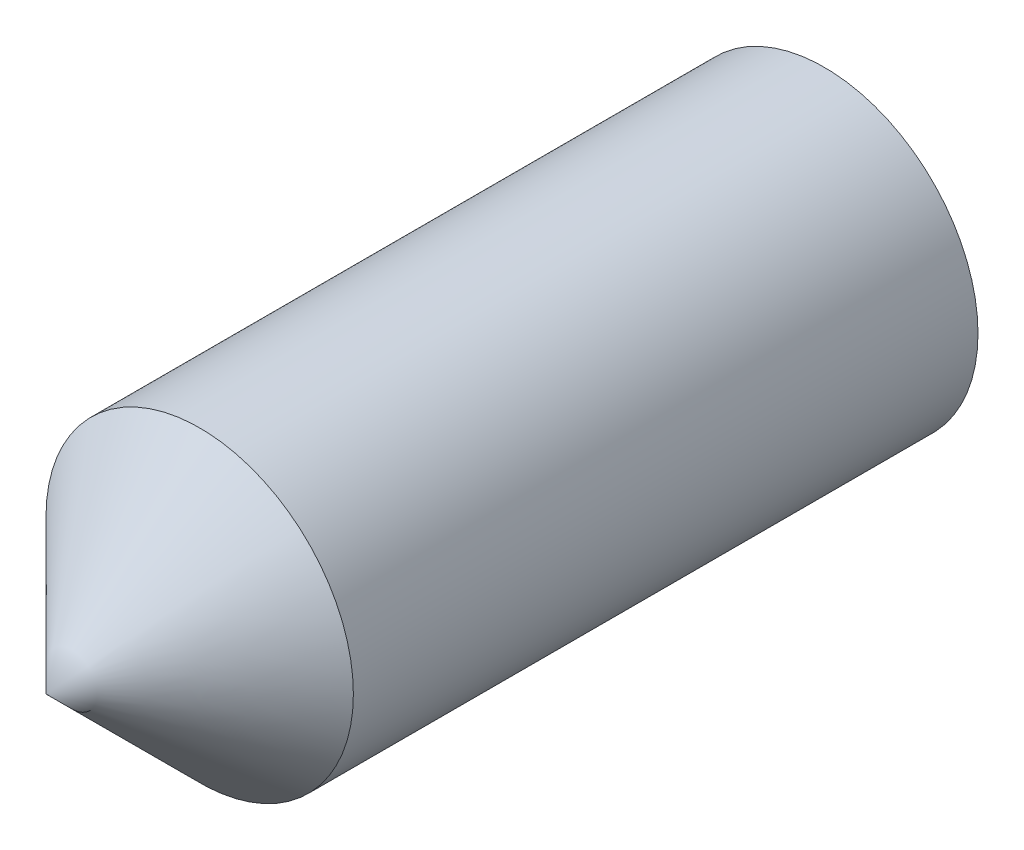
SolidWorks part; units mm, degrees
ref_plane "Front Plane" through (0, 0, 0) normal (0, 0, 1) x (1, 0, 0)
ref_plane "Top Plane" through (0, 0, 0) normal (0, 1, 0) x (1, 0, 0)
ref_plane "Right Plane" through (0, 0, 0) normal (1, 0, 0) x (0, 0, -1)
other "Configuration Table"
ref_plane "Plane1" through (0, 0, 40) normal (0, 0, 1) x (1, 0, 0)
ref_plane "Plane2" through (0, 33.5, 0) normal (0, 1, 0) x (1, 0, 0)
sketch "Sketch4" plane through (0, 33.5, 0) normal (0, 1, 0) x (1, 0, 0)
  line L0 (-10.8265, -40) -> (10.8265, -40) construction
  line L1 (0, -40) -> (9.8423, -40)
  line L2 (0, -40) -> (0, -80)
  line L3 (0, -80) -> (0, -89.8423)
  line L4 (9.8423, -40) -> (9.8423, -80)
  line L5 (0, -10.8265) -> (0, 10.8265) construction
  line L6 (9.8423, -80) -> (0, -89.8423)
revolve "Revolve1" add sketch "Sketch4" angle 360 about L2
